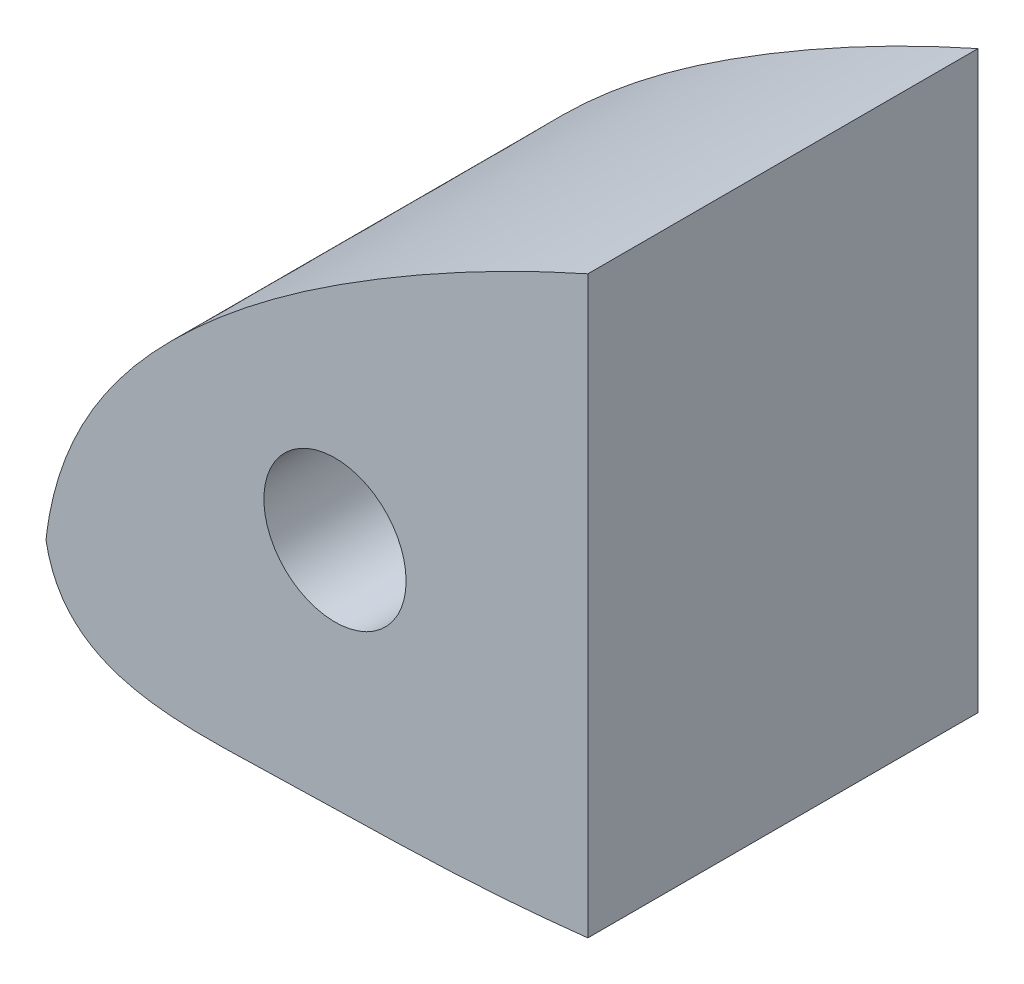
SolidWorks part; units mm, degrees
ref_plane "Front Plane" through (0, 0, 0) normal (0, 0, 1) x (1, 0, 0)
ref_plane "Top Plane" through (0, 0, 0) normal (0, 1, 0) x (1, 0, 0)
ref_plane "Right Plane" through (0, 0, 0) normal (1, 0, 0) x (0, 0, -1)
sketch "Sketch1" plane through (0, 0, 0) normal (0, 0, 1) x (1, 0, 0)
  spline S0 degree 3 poles (0.0006, 0.0001) (0.8106, 7.3592) (8.6491, 17.8566) (26.2867, 29.9752) (52.1111, 42.0692) (89.5976, 49.2908) (131.4008, 47.8848) (173.2567, 40.0411) (217.9611, 29.613) (256.9521, 19.5289) (290.3598, 8.711) (301.2732, 4.3828) (314.8169, -0.5162) (309.8463, 0.0001) knots 0 0 0 0 0.060864 0.113688 0.188609 0.312909 0.448482 0.557612 0.691544 0.852438 0.929756 0.976058 1 1 1 1
  spline S1 degree 3 poles (309.8463, 0.0001) (303.9568, 1.471) (293.9895, 2.094) (276.264, 4.5144) (260.8463, 5.4274) (235.8588, 7.8703) (205.1014, 8.8381) (157.7186, 9.0307) (110.4973, 6.1815) (66.5062, -0.5867) (36.4547, -6.0985) (15.3166, -6.1891) (1.2307, -6.9241) (0.0006, 0.0001) knots 0 0 0 0 0.057787 0.095275 0.171021 0.205339 0.335319 0.464904 0.658702 0.785512 0.893517 0.943092 1 1 1 1
extrude "Boss-Extrude1" add sketch "Sketch1" along normal blind 27.432
sketch "Sketch2" plane through (0, 0, 27.432) normal (0, 0, 1) x (1, 0, 0)
  circle A0 centre (20.32, 10.16) radius 5
  circle A1 centre (227.2963, 19.0501) radius 3.175
  dimension "D2" = 10
  dimension "D3" = 6.35
  dimension "D6" = 20.32
  dimension "D1" = 82.55
  dimension "D4" = 19.05
  dimension "D5" = 10.16
extrude "Cut-Extrude1" cut sketch "Sketch2" against normal through all
sketch "Sketch3" plane through (0, 0, 27.432) normal (0, 0, 1) x (1, 0, 0)
  line L1 (38.1, 71.718) -> (331.2889, 71.718)
  line L2 (38.1, 71.718) -> (38.1, -66.2532)
  line L3 (38.1, -66.2532) -> (331.2889, -66.2532)
  line L4 (331.2889, 71.718) -> (331.2889, -66.2532)
  dimension "D1" = 38.1
extrude "Cut-Extrude2" cut sketch "Sketch3" against normal through all
